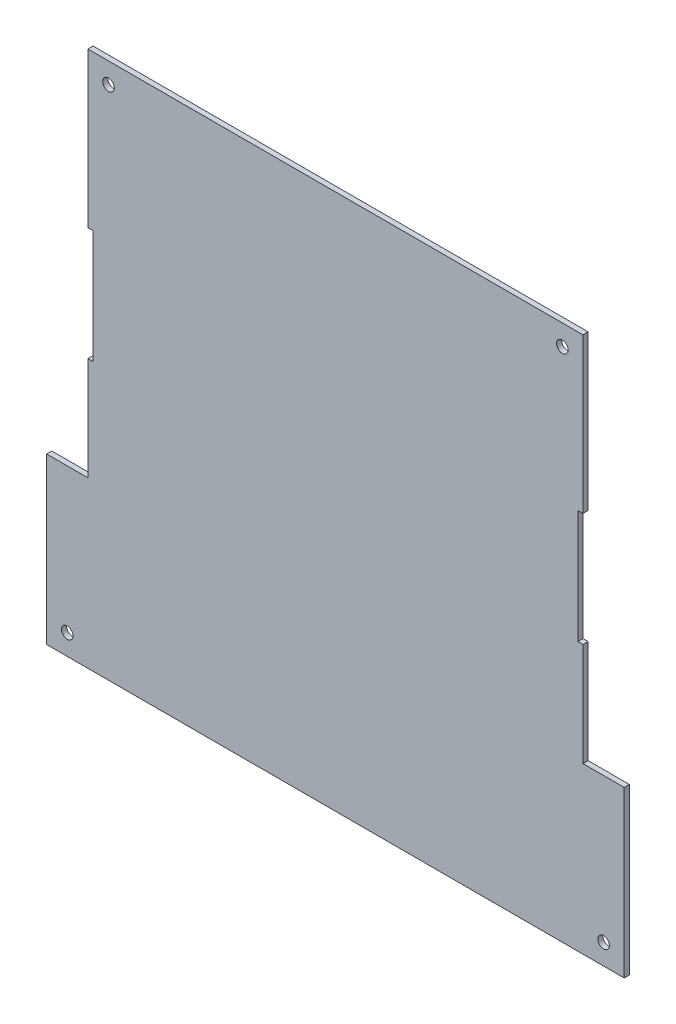
SolidWorks part; units mm, degrees
material "Acrylic (Medium-high impact)"
ref_plane "Front Plane" through (0, 0, 0) normal (0, 0, 1) x (1, 0, 0)
ref_plane "Top Plane" through (0, 0, 0) normal (0, 1, 0) x (1, 0, 0)
ref_plane "Right Plane" through (0, 0, 0) normal (1, 0, 0) x (0, 0, -1)
sketch "Sketch1" plane through (0, 0, 0) normal (0, 0, 1) x (1, 0, 0)
  line L1 (0, 0) -> (304.8, 0)
  line L2 (0, 0) -> (0, -330.2)
  line L3 (0, -330.2) -> (304.8, -330.2)
  line L4 (304.8, 0) -> (304.8, -330.2)
  dimension "D1" = 304.8
  dimension "D2" = 330.2
extrude "Boss-Extrude1" add sketch "Sketch1" along normal blind 3.175
sketch "Sketch2" plane through (0, 0, 3.175) normal (0, 0, 1) x (1, 0, 0)
  line L0 (152.4, 0) -> (152.4, -330.2) construction
  line L1 (304.8, 0) -> (0, 0) construction
  line L2 (0, -330.2) -> (304.8, -330.2) construction
  line L3 (0, -165.1) -> (304.8, -165.1) construction
  line L4 (0, 0) -> (0, -330.2) construction
  line L5 (304.8, -330.2) -> (304.8, 0) construction
  point P0 (12.7, -12.7)
  point P13 (292.1, -12.7)
  point P15 (292.1, -317.5)
  point P16 (12.7, -317.5)
  dimension "D1" = 12.7
  dimension "D2" = 12.7
hole_wizard "1/4 Clearance Hole1" positions "Sketch2" profile "Sketch3" hole size "1/4" standard "ANSI Inch"
sketch "Sketch3" plane through (12.7, -12.7, 3.175) normal (1, 0, 0) x (0, -1, 0)
  line L0 (0, 0) -> (0, 3.175)
  line L1 (0, 3.175) -> (3.5712, 3.175)
  line L2 (3.5712, 3.175) -> (3.5712, 0)
  line L5 (3.5712, 0) -> (0, 0)
  line L11 (0, -6.35) -> (0, 107.95) construction
  dimension "Thru Hole Dia." = 7.1425
  dimension "Thru Hole Depth" = 3.175
sketch "Sketch4" plane through (0, 0, 3.175) normal (0, 0, 1) x (1, 0, 0)
  line L0 (152.4, 0) -> (152.4, -330.2) construction
  line L1 (304.8, 0) -> (0, 0) construction
  line L2 (0, -330.2) -> (304.8, -330.2) construction
  line L3 (0, -165.1) -> (304.8, -165.1) construction
  line L4 (0, 0) -> (0, -330.2) construction
  line L6 (301.625, -165.1) -> (304.8, -165.1)
  line L7 (3.175, -165.1) -> (0, -165.1)
  line L8 (3.175, -165.1) -> (3.175, -95.25)
  line L9 (3.175, -95.25) -> (0, -95.25)
  line L10 (0, -165.1) -> (0, -95.25)
  line L11 (304.8, -165.1) -> (304.8, -95.25)
  line L12 (301.625, -165.1) -> (301.625, -95.25)
  line L13 (301.625, -95.25) -> (304.8, -95.25)
  dimension "D1" = 69.85
  dimension "D2" = 3.175
extrude "Cut-Extrude1" cut sketch "Sketch4" against normal up to next
sketch "Sketch5" plane through (0, 0, 3.175) normal (0, 0, 1) x (1, 0, 0)
  line L0 (152.4, 0) -> (152.4, -330.2) construction
  line L1 (0, -330.2) -> (-25.4, -330.2)
  line L2 (0, -330.2) -> (0, -228.6)
  line L3 (0, -228.6) -> (-25.4, -228.6)
  line L4 (-25.4, -330.2) -> (-25.4, -228.6)
  line L5 (304.8, 0) -> (0, 0) construction
  line L6 (0, -330.2) -> (304.8, -330.2) construction
  line L7 (304.8, -228.6) -> (330.2, -228.6)
  line L8 (330.2, -330.2) -> (330.2, -228.6)
  line L9 (304.8, -330.2) -> (330.2, -330.2)
  line L10 (304.8, -330.2) -> (304.8, -228.6)
  dimension "D1" = 25.4
  dimension "D2" = 101.6
extrude "Boss-Extrude2" add sketch "Sketch5" against normal up to surface (3.175 mm away) up to face at (16.2712, -12.7, 0)
sketch "Sketch6" plane through (0, 0, 3.175) normal (0, 0, 1) x (1, 0, 0)
  line L0 (152.4, 0) -> (152.4, -330.2) construction
  line L1 (304.8, 0) -> (0, 0) construction
  line L2 (-25.4, -330.2) -> (330.2, -330.2) construction
  line L3 (-25.4, -228.6) -> (-25.4, -330.2) construction
  point P6 (-12.7, -317.5)
  point P10 (317.5, -317.5)
  dimension "D1" = 12.7
  dimension "D2" = 12.7
hole_wizard "1/4 Clearance Hole2" positions "Sketch6" profile "Sketch7" hole size "1/4" standard "ANSI Inch" end condition up to next
sketch "Sketch7" plane through (317.5, -317.5, 3.175) normal (1, 0, 0) x (0, -1, 0)
  line L0 (0, 0) -> (0, 3.175)
  line L1 (0, 3.175) -> (3.5712, 3.175)
  line L2 (3.5712, 3.175) -> (3.5712, 0)
  line L5 (3.5712, 0) -> (0, 0)
  line L11 (0, -6.35) -> (0, 107.95) construction
  dimension "Thru Hole Dia." = 7.1425
  dimension "Thru Hole Depth" = 3.175
